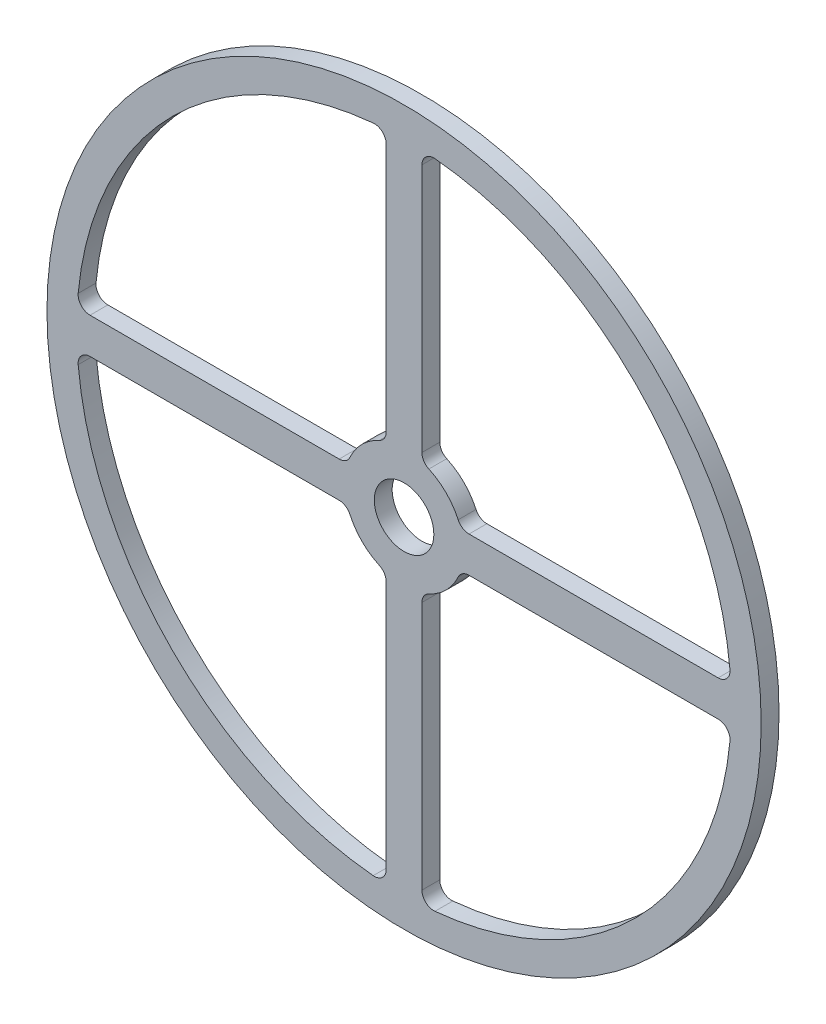
SolidWorks part; units mm, degrees
ref_plane "前视基准面" through (0, 0, 0) normal (0, 0, 1) x (1, 0, 0)
ref_plane "上视基准面" through (0, 0, 0) normal (0, 1, 0) x (1, 0, 0)
ref_plane "右视基准面" through (0, 0, 0) normal (1, 0, 0) x (0, 0, -1)
sketch "草图1" plane through (0, 0, 0) normal (0, 0, 1) x (1, 0, 0)
  line L0 (3, 54.9181) -> (3, 9.5394)
  line L1 (9.5394, 3) -> (54.9181, 3)
  line L2 (0, 72.2615) -> (0, -79.5295) construction
  line L3 (-78.2791, 0) -> (88.2263, 0) construction
  line L4 (-9.5394, -3) -> (-54.9181, -3)
  line L5 (9.5394, -3) -> (54.9181, -3)
  line L7 (-3, 9.5394) -> (-3, 54.9181)
  line L8 (-3, -9.5394) -> (-3, -54.9181)
  line L9 (3, -9.5394) -> (3, -54.9181)
  line L10 (-9.5394, 3) -> (-54.9181, 3)
  circle A0 centre (0, 0) radius 60
  arc A1 (-3, 54.9181) -> (-54.9181, 3) centre (0, 0) ccw
  arc A2 (3, -54.9181) -> (54.9181, -3) centre (0, 0) ccw
  arc A3 (-54.9181, -3) -> (-3, -54.9181) centre (0, 0) ccw
  arc A4 (54.9181, 3) -> (3, 54.9181) centre (0, 0) ccw
  arc A5 (-3, 9.5394) -> (-9.5394, 3) centre (0, 0) ccw
  circle A6 centre (0, 0) radius 5
  arc A7 (9.5394, 3) -> (3, 9.5394) centre (0, 0) ccw
  arc A8 (-9.5394, -3) -> (-3, -9.5394) centre (0, 0) ccw
  arc A9 (3, -9.5394) -> (9.5394, -3) centre (0, 0) ccw
  dimension "D1" = 120
  dimension "D2" = 110
  dimension "D5" = 10
  dimension "D6" = 20
  dimension "D3" = 3
  dimension "D4" = 3
extrude "凸台-拉伸1" add sketch "草图1" along normal blind 3
fillet "圆角1" radius 2 1 edges at (3, 54.9181, 1.5)
fillet "圆角2" radius 2 7 edges at (54.9181, 3, 1.5) (54.9181, -3, 1.5) (3, -54.9181, 1.5) (-3, -54.9181, 1.5) (-54.9181, -3, 1.5) (-54.9181, 3, 1.5) (-3, 54.9181, 1.5)
fillet "圆角4" radius 2 8 edges at (3, -9.5394, 1.5) (-3, -9.5394, 1.5) (-9.5394, -3, 1.5) (-9.5394, 3, 1.5) (-3, 9.5394, 1.5) (3, 9.5394, 1.5) (9.5394, 3, 1.5) (9.5394, -3, 1.5)
